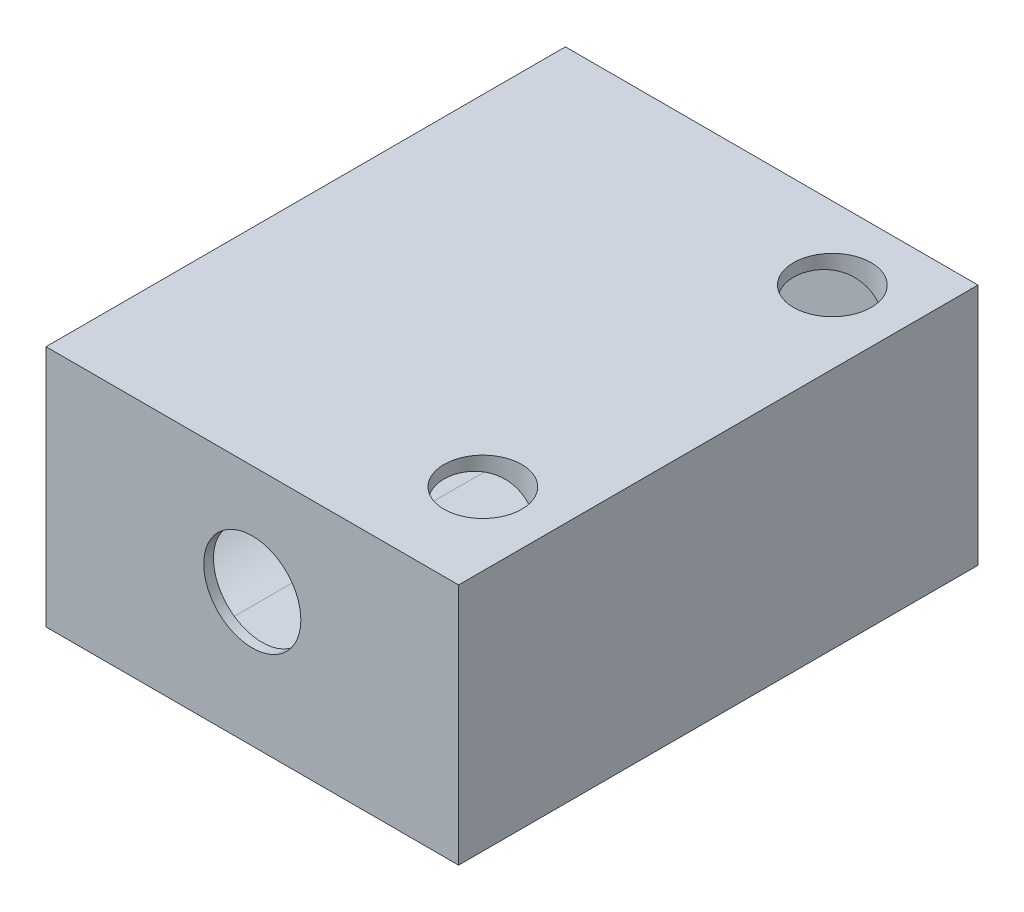
SolidWorks part; units mm, degrees
ref_plane "Front Plane" through (0, 0, 0) normal (0, 0, 1) x (1, 0, 0)
ref_plane "Top Plane" through (0, 0, 0) normal (0, 1, 0) x (1, 0, 0)
ref_plane "Right Plane" through (0, 0, 0) normal (1, 0, 0) x (0, 0, -1)
sketch "Sketch1" plane through (0, 0, 0) normal (0, 0, 1) x (1, 0, 0)
  line L1 (0, 0) -> (107.95, 0)
  line L2 (0, 0) -> (0, 63.5)
  line L3 (0, 63.5) -> (107.95, 63.5)
  line L4 (107.95, 0) -> (107.95, 63.5)
  dimension "D1" = 63.5
  dimension "D2" = 107.95
extrude "Boss-Extrude5" add sketch "Sketch1" along normal blind 133.35
sketch "Sketch5" plane through (0, 0, 133.35) normal (0, 0, 1) x (1, 0, 0)
  line L0 (31.75, 60.325) -> (76.2, 60.325)
  line L1 (0, 63.5) -> (107.95, 63.5)
  line L2 (0, 63.5) -> (0, 0)
  line L3 (0, 0) -> (107.95, 0)
  line L4 (107.95, 63.5) -> (107.95, 0)
  line L5 (31.75, 9.525) -> (76.2, 9.525)
  arc A0 (31.75, 60.325) -> (31.75, 9.525) centre (31.75, 34.925) ccw
  arc A1 (76.2, 9.525) -> (76.2, 60.325) centre (76.2, 34.925) ccw
  dimension "D1" = 50.8
  dimension "D2" = 50.8
  dimension "D3" = 31.75
  dimension "D4" = 31.75
  dimension "D5" = 34.925
  dimension "D6" = 34.925
  dimension "D7" = 44.45
extrude "Cut-Extrude4" cut sketch "Sketch5" against normal blind 128.27 flip side to cut
sketch "Sketch6" plane through (0, 0, 133.35) normal (0, 0, 1) x (1, 0, 0)
  line L1 (0, 0) -> (107.95, 0)
  line L2 (0, 0) -> (0, 63.5)
  line L3 (0, 63.5) -> (107.95, 63.5)
  line L4 (107.95, 0) -> (107.95, 63.5)
  circle A0 centre (53.975, 34.925) radius 12.7
  dimension "D1" = 25.4
  dimension "D2" = 53.975
extrude "Boss-Extrude6" add sketch "Sketch6" along normal blind 2.54
sketch "Sketch8" plane through (0, 63.5, 0) normal (0, -1, 0) x (1, 0, 0)
  line L6 (0, 135.89) -> (107.95, 135.89) construction
  line L7 (0, 0) -> (107.95, 0) construction
  line L9 (107.95, 135.89) -> (107.95, 0) construction
  circle A0 centre (88.9, 19.05) radius 10.16
  circle A1 centre (88.9, 110.49) radius 10.16
  dimension "D1" = 20.32
  dimension "D2" = 20.32
  dimension "D3" = 25.4
  dimension "D4" = 19.05
  dimension "D5" = 19.05
extrude "Cut-Extrude6" cut sketch "Sketch8" along normal up to next
